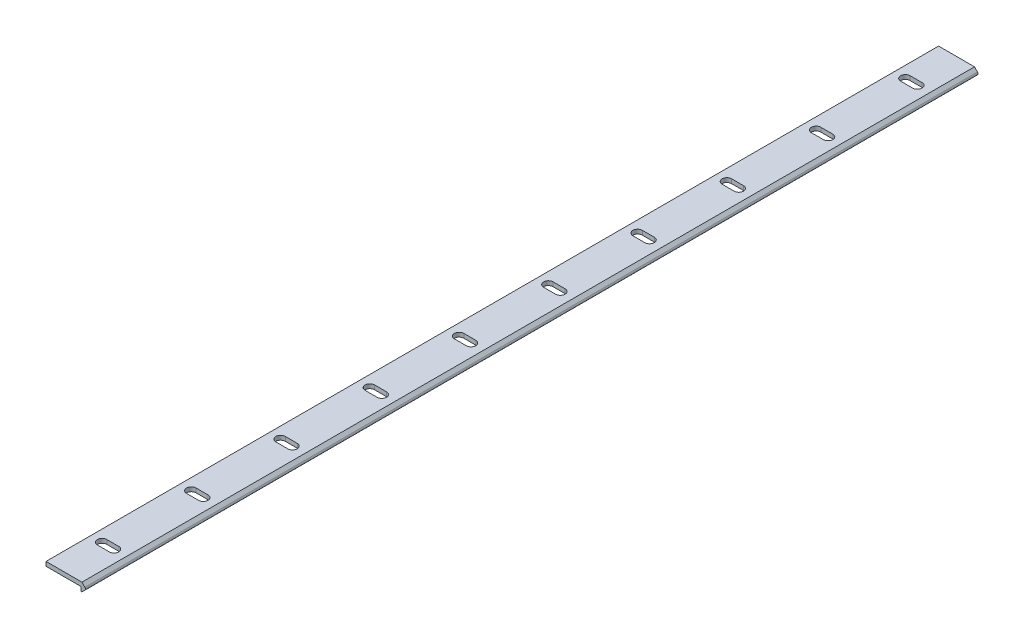
SolidWorks part; units mm, degrees
material "6061-T6 (SS)"
ref_plane "Front Plane" through (0, 0, 0) normal (0, 0, 1) x (1, 0, 0)
ref_plane "Top Plane" through (0, 0, 0) normal (0, 1, 0) x (1, 0, 0)
ref_plane "Right Plane" through (0, 0, 0) normal (1, 0, 0) x (0, 0, -1)
sketch "Sketch1" plane through (0, 0, 0) normal (0, 0, 1) x (1, 0, 0)
  line L0 (19.5291, 0) -> (19.5291, 4.75) construction
  line L1 (0, 0) -> (22.497, 0) construction
  line L2 (0, 0) -> (0, 4.75) construction
  line L3 (0, 4.75) -> (22.497, 4.75) construction
  line L4 (22.497, 0) -> (22.497, 4.75) construction
  line L5 (19.5291, 2.375) -> (0, 2.375)
  line L6 (19.5291, 2.375) -> (19.5291, 0)
  line L7 (19.5291, 4.75) -> (20.122, 4.75)
  line L8 (20.122, 4.75) -> (22.497, 2.375)
  line L9 (19.5291, 4.75) -> (0, 4.75)
  line L10 (0, 4.75) -> (0, 2.375)
  line L11 (22.497, 2.375) -> (20.122, 0)
  line L12 (20.122, 0) -> (19.5291, 0)
  dimension "D1" = 22.497
  dimension "D2" = 4.75
  dimension "D3" = 19.5291
  dimension "D4" = 90
extrude "Boss-Extrude1" add sketch "Sketch1" along normal blind 500
sketch "Sketch2" plane through (0, 4.75, 0) normal (0, 1, 0) x (1, 0, 0)
  line L0 (0, -500) -> (0, 0) construction
  line L1 (20.122, 0) -> (0, 0) construction
  line L2 (6.4087, -25) -> (9.7587, -25)
  line L3 (9.7587, -25) -> (13.1087, -25)
  line L4 (6.4087, -22.35) -> (13.1087, -22.35)
  line L5 (13.1087, -27.65) -> (6.4087, -27.65)
  circle A0 centre (9.7587, -25) radius 2.65 construction
  circle A1 centre (13.1087, -25) radius 2.65 construction
  circle A2 centre (6.4087, -25) radius 2.65 construction
  arc A3 (6.4087, -22.35) -> (6.4087, -27.65) centre (6.4087, -25) ccw
  arc A4 (13.1087, -22.35) -> (13.1087, -27.65) centre (13.1087, -25) cw
  point P4 (10.061, 0)
  dimension "D3" = 5.3
  dimension "D1" = 9.7587
  dimension "D2" = 25
  dimension "D4" = 6.7
extrude "Cut-Extrude1" cut sketch "Sketch2" against normal blind 2.375
pattern_linear "LPattern1" count 10 spacing 50 along (0, 0, 1) of "Cut-Extrude1"
fillet "Fillet1" radius 1 1 edges at (22.497, 2.375, 250)
